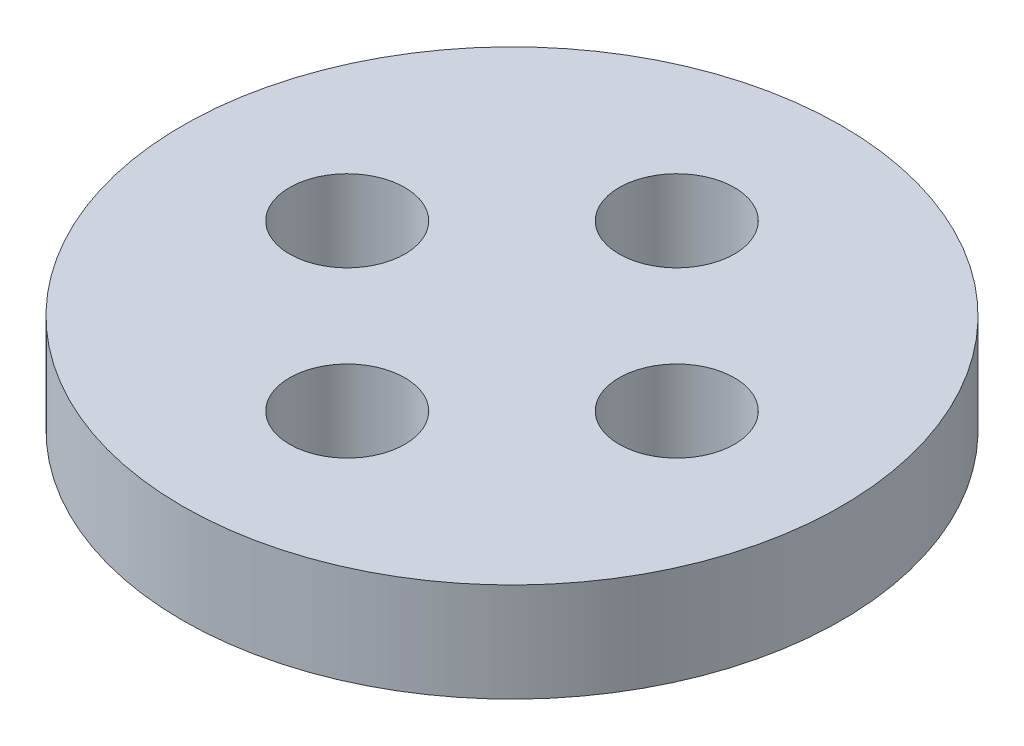
SolidWorks part; units mm, degrees
ref_plane "Front Plane" through (0, 0, 0) normal (0, 0, 1) x (1, 0, 0)
ref_plane "Top Plane" through (0, 0, 0) normal (0, 1, 0) x (1, 0, 0)
ref_plane "Right Plane" through (0, 0, 0) normal (1, 0, 0) x (0, 0, -1)
sketch "Sketch1" plane through (0, 0, 0) normal (0, 1, 0) x (1, 0, 0)
  circle A0 centre (0, 0) radius 10
  circle A1 centre (0, 5) radius 1.75
  circle A2 centre (5, 0) radius 1.75
  circle A3 centre (0, -5) radius 1.75
  circle A4 centre (-5, 0) radius 1.75
  point P14 (0, 0)
  dimension "D1" = 20
  dimension "D2" = 3.5
  dimension "D3" = 5
  dimension "D5" = 5
  dimension "D6" = 5
  dimension "D4" = 4
extrude "Boss-Extrude1" add sketch "Sketch1" along normal blind 3
